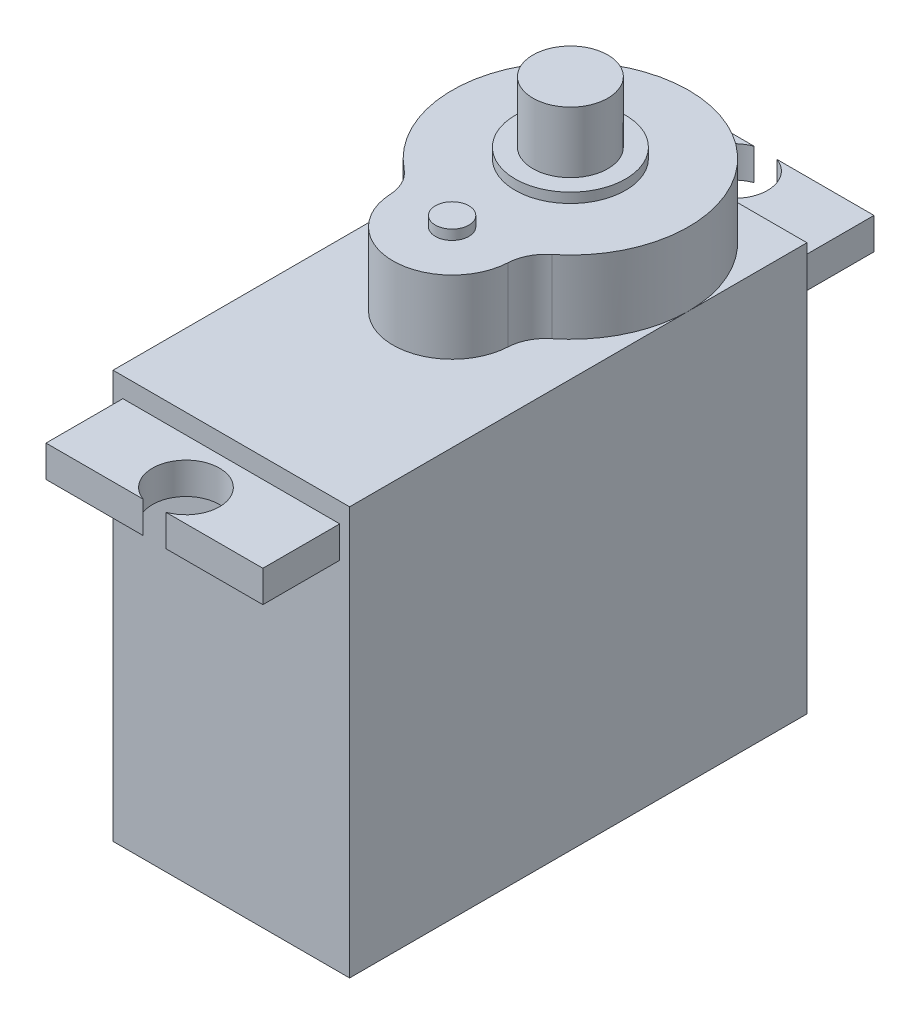
SolidWorks part; units mm, degrees
ref_plane "Front Plane" through (0, 0, 0) normal (0, 0, 1) x (1, 0, 0)
ref_plane "Top Plane" through (0, 0, 0) normal (0, 1, 0) x (1, 0, 0)
ref_plane "Right Plane" through (0, 0, 0) normal (1, 0, 0) x (0, 0, -1)
sketch "Sketch1" plane through (0, 0, 0) normal (0, 1, 0) x (1, 0, 0)
  line L1 (0, 0) -> (12, 0)
  line L2 (0, 0) -> (0, 23.2)
  line L3 (0, 23.2) -> (12, 23.2)
  line L4 (12, 0) -> (12, 23.2)
  dimension "D1" = 12
  dimension "D2" = 23.2
extrude "Boss-Extrude1" add sketch "Sketch1" along normal blind 20.7
sketch "Sketch2" plane through (0, 0, 0) normal (0, 0, 1) x (1, 0, 0)
  line L1 (0.5, 19.7) -> (11.5, 19.7)
  line L2 (0.5, 19.7) -> (0.5, 18.1)
  line L3 (0.5, 18.1) -> (11.5, 18.1)
  line L4 (11.5, 19.7) -> (11.5, 18.1)
  line L5 (0, 20.7) -> (0, 0) construction
  line L6 (0, 20.7) -> (12, 20.7) construction
  dimension "D1" = 11
  dimension "D2" = 1.6
  dimension "D3" = 0.5
  dimension "D4" = 1
extrude "Boss-Extrude2" add sketch "Sketch2" along normal blind 3.9
sketch "Sketch3" plane through (0, 0, -23.2) normal (0, 0, -1) x (-1, 0, 0)
  line L0 (-12, 20.7) -> (0, 20.7) construction
  line L1 (-11.5, 19.7) -> (-0.5, 19.7)
  line L2 (-11.5, 19.7) -> (-11.5, 18.1)
  line L3 (-11.5, 18.1) -> (-0.5, 18.1)
  line L4 (-0.5, 19.7) -> (-0.5, 18.1)
  line L7 (-12, 20.7) -> (-12, 0) construction
  dimension "D2" = 1.6
  dimension "D1" = 1
  dimension "D3" = 11
  dimension "D4" = 0.5
extrude "Boss-Extrude3" add sketch "Sketch3" along normal blind 3.9
sketch "Sketch4" plane through (0, 20.7, 0) normal (0, 1, 0) x (1, 0, 0)
  line L0 (12, 23.2) -> (0, 23.2) construction
  line L1 (0, 23.2) -> (0, 0) construction
  circle A0 centre (6, 17.2) radius 6
  dimension "D1" = 12
  dimension "D2" = 6
  dimension "D3" = 6
extrude "Boss-Extrude4" add sketch "Sketch4" along normal blind 3.7
sketch "Sketch5" plane through (0, 20.7, 0) normal (0, 1, 0) x (1, 0, 0)
  circle A0 centre (6, 11.2) radius 3
  arc A1 (0, 17.2) -> (12, 17.2) centre (6, 17.2) ccw construction
  dimension "D1" = 6
extrude "Boss-Extrude5" add sketch "Sketch5" along normal blind 3.7
fillet "Fillet1" radius 2 2 edges at (3.0953, 22.55, -11.95) (8.9047, 22.55, -11.95)
sketch "Sketch6" plane through (0, 24.4, 0) normal (0, 1, 0) x (1, 0, 0)
  circle A0 centre (6, 11.2) radius 0.85
  dimension "D1" = 1.7
extrude "Boss-Extrude6" add sketch "Sketch6" along normal blind 0.5
sketch "Sketch7" plane through (0, 24.4, 0) normal (0, 1, 0) x (1, 0, 0)
  circle A0 centre (6, 17.2) radius 2.8
  dimension "D1" = 5.6
extrude "Boss-Extrude7" add sketch "Sketch7" along normal blind 0.5
sketch "Sketch8" plane through (0, 24.9, 0) normal (0, 1, 0) x (1, 0, 0)
  circle A0 centre (6, 17.2) radius 1.9
  dimension "D1" = 3.8
extrude "Boss-Extrude8" add sketch "Sketch8" along normal blind 3.1
hole_wizard "M3 Clearance Hole1" positions "Sketch9" profile "Sketch10" hole size "M3" standard "ANSI Metric"
sketch "Sketch9" plane through (0, 19.7, 0) normal (0, 1, 0) x (1, 0, 0)
  line L0 (0.5, -3.9) -> (0.5, 0) construction
  line L1 (11.5, 0) -> (0.5, 0) construction
  line L2 (0.5, 27.1) -> (0.5, 23.2) construction
  line L3 (0.5, 23.2) -> (11.5, 23.2) construction
  point P0 (6, -2.3)
  point P7 (6, 25.5)
  dimension "D1" = 5.5
  dimension "D2" = 2.3
  dimension "D3" = 5.5
  dimension "D4" = 2.3
sketch "Sketch10" plane through (6, 19.7, 2.3) normal (1, 0, 0) x (0, 0, 1)
  line L0 (0, 0) -> (0, 4.0215)
  line L1 (0, 4.0215) -> (1.7, 3)
  line L2 (1.7, 3) -> (1.7, 0)
  line L5 (1.7, 0) -> (0, 0)
  line L10 (0, 4.0215) -> (-1.7, 3) construction
  line L11 (0, -6.35) -> (0, 107.95) construction
  dimension "Hole Dia." = 3.4
  dimension "Hole Depth" = 3
  dimension "Drill Angle" = 118
sketch "Sketch11" plane through (0, 0, -23.2) normal (0, 0, -1) x (-1, 0, 0)
  line L0 (-12, 0) -> (0, 0) construction
  line L5 (0, 20.7) -> (0, 0) construction
  circle A0 centre (-7, 4.2) radius 0.5
  dimension "D1" = 1
  dimension "D2" = 4.2
  dimension "D3" = 7
extrude "Boss-Extrude9" add sketch "Sketch11" along normal blind 3
pattern_linear "LPattern2" count 3 spacing 1.01 along (-1, 0, 0) of "Boss-Extrude9"
equation "\"laser\"= 0.18'Laser Kerf"
equation "\"D3@Sketch2\"=(\"D1@Sketch1\"-\"D1@Sketch2\")/2"
equation "\"D4@Sketch3\"=\"D3@Sketch2\""
equation "\"D1@Sketch4\"=\"D1@Sketch1\""
equation "\"D2@Sketch4\"=\"D1@Sketch4\"/2"
equation "\"D3@Sketch4\"=\"D1@Sketch1\"/2"
equation "\"D1@Sketch9\"=\"D1@Sketch2\"/2"
equation "\"D3@Sketch9\"=\"D1@Sketch9\""
equation "\"D4@Sketch9\"=\"D2@Sketch9\""
